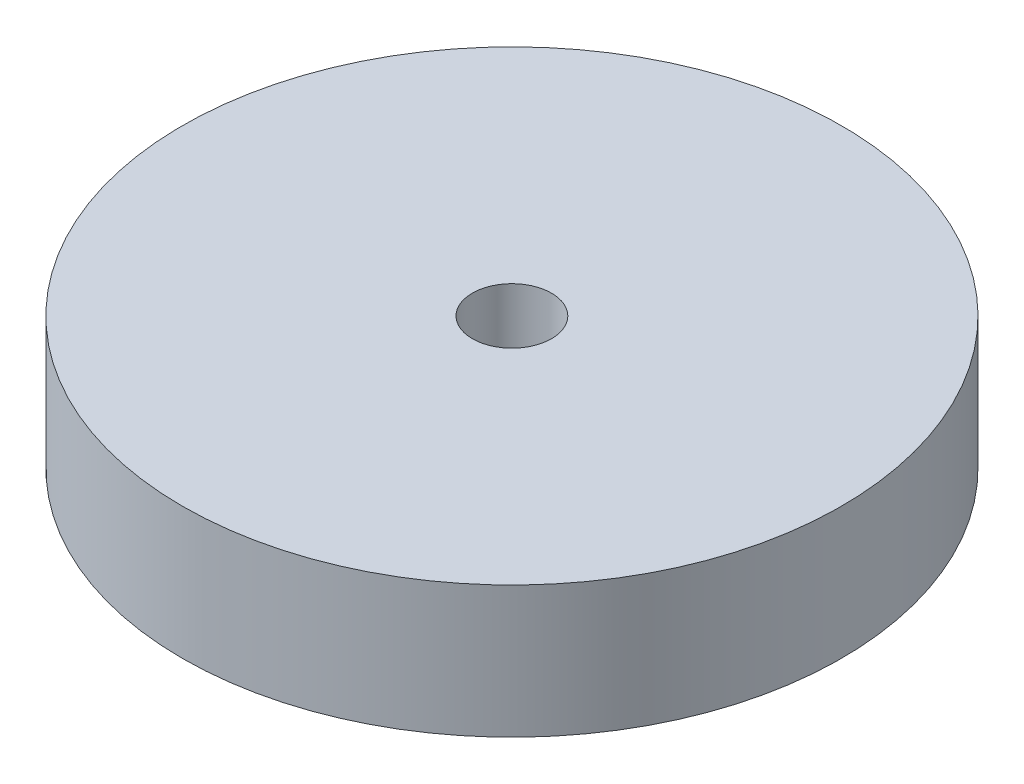
SolidWorks part; units mm, degrees
material "AISI 316 Stainless Steel Sheet (SS)"
ref_plane "Front Plane" through (0, 0, 0) normal (0, 0, 1) x (1, 0, 0)
ref_plane "Top Plane" through (0, 0, 0) normal (0, 1, 0) x (1, 0, 0)
ref_plane "Right Plane" through (0, 0, 0) normal (1, 0, 0) x (0, 0, -1)
sketch "Sketch1" plane through (0, 0, 0) normal (1, 0, 0) x (0, 0, -1)
  line L0 (0, 265.4221) -> (0, -191.5584) construction
  line L1 (-30, 50) -> (-30, -50)
  line L2 (-30, -50) -> (-250, -50)
  line L3 (-250, -50) -> (-250, 50)
  line L4 (-250, 50) -> (-30, 50)
  point P5 (-30, 0)
  dimension "D1" = 250
  dimension "D2" = 30
  dimension "D3" = 100
revolve "Revolve1" add sketch "Sketch1" angle 360 about L0
